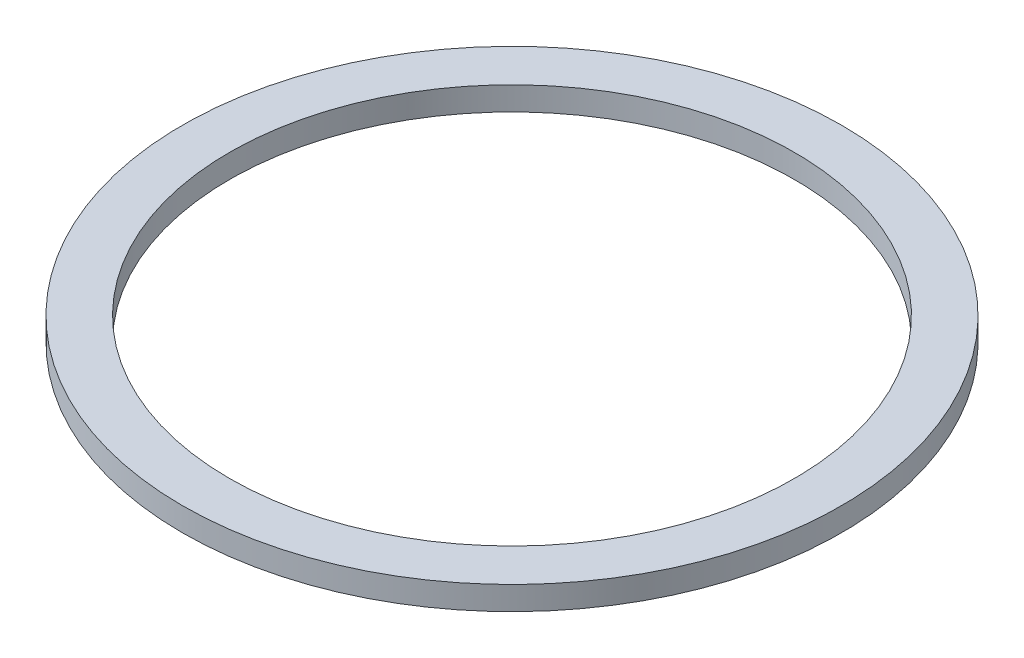
SolidWorks part; units mm, degrees
material "201 Annealed Stainless Steel (SS)"
ref_plane "Front Plane" through (0, 0, 0) normal (0, 0, 1) x (1, 0, 0)
ref_plane "Top Plane" through (0, 0, 0) normal (0, 1, 0) x (1, 0, 0)
ref_plane "Right Plane" through (0, 0, 0) normal (1, 0, 0) x (0, 0, -1)
sketch "Sketch1" plane through (0, 0, 0) normal (0, 1, 0) x (1, 0, 0)
  circle A0 centre (0, 0) radius 6
  circle A1 centre (0, 0) radius 7
  dimension "D1" = 14
  dimension "D2" = 12
extrude "Boss-Extrude1" add sketch "Sketch1" along normal mid plane 0.5
